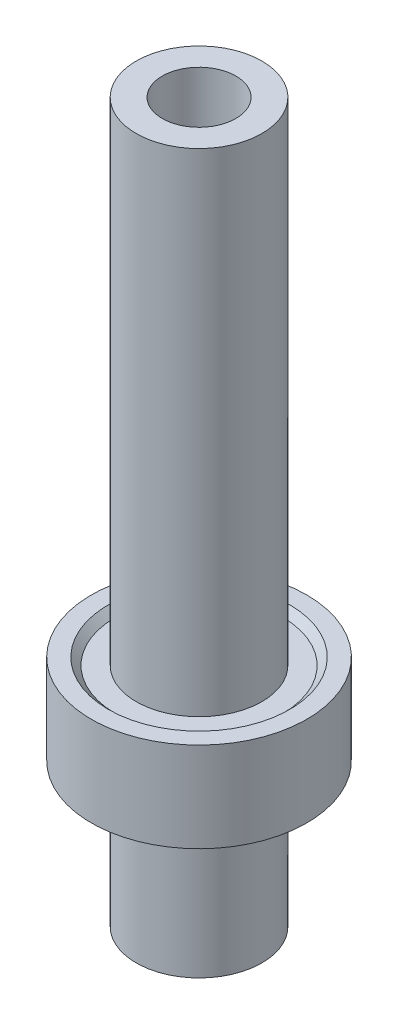
SolidWorks part; units mm, degrees
material "Cast Alloy Steel"
ref_plane "Front Plane" through (0, 0, 0) normal (0, 0, 1) x (1, 0, 0)
ref_plane "Top Plane" through (0, 0, 0) normal (0, 1, 0) x (1, 0, 0)
ref_plane "Right Plane" through (0, 0, 0) normal (1, 0, 0) x (0, 0, -1)
sketch "Sketch1" plane through (0, 0, 0) normal (1, 0, 0) x (0, 0, -1)
  line L0 (0, 0) -> (0, 62.475) construction
  line L1 (0, 33) -> (0, -33) construction
  line L2 (10.25, 0) -> (10.25, 200)
  line L3 (10.25, 200) -> (17.5, 200)
  line L4 (17.5, 200) -> (17.5, 63)
  line L5 (25.25, 65) -> (30, 65)
  line L6 (30, 65) -> (30, 40)
  line L7 (30, 40) -> (17.5, 40)
  line L8 (17.5, 40) -> (17.5, 0)
  line L9 (17.5, 0) -> (10.25, 0)
  line L10 (25.25, 65) -> (17.5, 63) construction
  line L11 (25.25, 65) -> (23.25, 63)
  line L12 (23.25, 63) -> (17.5, 63)
  dimension "D1" = 20.5
  dimension "D2" = 35
  dimension "D3" = 200
  dimension "D4" = 60
  dimension "D5" = 25
  dimension "D6" = 50.5
  dimension "D7" = 23
  dimension "D8" = 40
  dimension "D9" = 45
revolve "Revolve1" add sketch "Sketch1" angle 360 about L0
